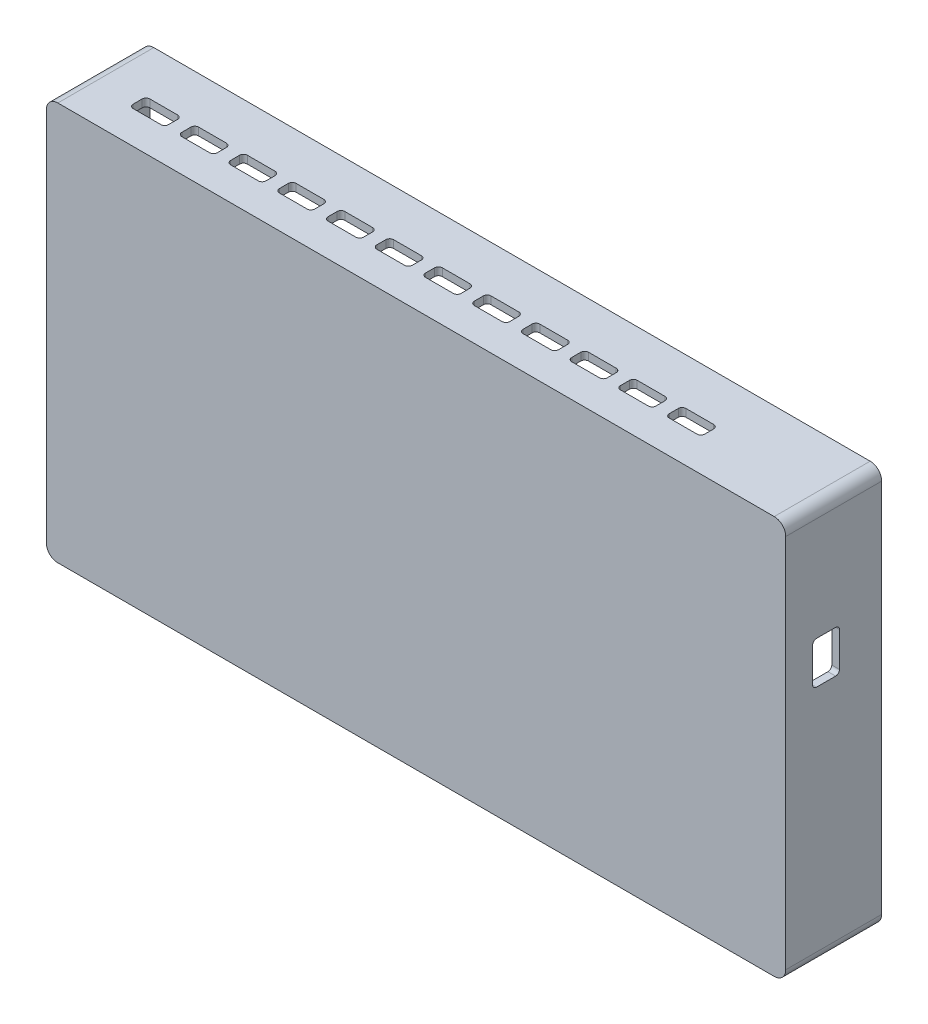
SolidWorks part; units mm, degrees
ref_plane "Front Plane" through (0, 0, 0) normal (0, 0, 1) x (1, 0, 0)
ref_plane "Top Plane" through (0, 0, 0) normal (0, 1, 0) x (1, 0, 0)
ref_plane "Right Plane" through (0, 0, 0) normal (1, 0, 0) x (0, 0, -1)
sketch "Sketch2" plane through (0, 0, 0) normal (0, 0, 1) x (1, 0, 0)
  line L8 (-189.174, -3.5) -> (3.5, -3.5)
  line L9 (3.5, -3.5) -> (3.5, 100.274)
  line L10 (3.5, 100.274) -> (-189.174, 100.274)
  line L11 (-189.174, 100.274) -> (-189.174, -3.5)
  line L12 (-186.174, -3.5) -> (0.5, -3.5)
  line L13 (3.5, -0.5) -> (3.5, 97.274)
  line L14 (0.5, 100.274) -> (-186.174, 100.274)
  line L15 (-189.174, 97.274) -> (-189.174, -0.5)
  arc A0 (-186.174, -3.5) -> (-189.174, -0.5) centre (-186.174, -0.5) cw
  arc A1 (0.5, -3.5) -> (3.5, -0.5) centre (0.5, -0.5) ccw
  arc A2 (3.5, 97.274) -> (0.5, 100.274) centre (0.5, 97.274) ccw
  arc A3 (-186.174, 100.274) -> (-189.174, 97.274) centre (-186.174, 97.274) ccw
  dimension "D2" = 3
  dimension "D1" = 3.5
extrude "Boss-Extrude1" add sketch "Sketch2" along normal blind 2 from offset 5
sketch "Sketch5" plane through (0, 0, 5) normal (0, 0, -1) x (-1, 0, 0)
  circle A0 centre (7.366, 91.059) radius 1.35
  circle A1 centre (7.366, 4.699) radius 1.35
  circle A2 centre (104.648, 42.799) radius 1.35
  circle A3 centre (179.578, 75.565) radius 1.35
  circle A4 centre (179.324, 5.207) radius 1.35
sketch "Sketch11" plane through (0, 0, 5) normal (0, 0, -1) x (-1, 0, 0)
  circle A0 centre (7.366, 91.059) radius 3
  circle A1 centre (7.366, 4.699) radius 3
  circle A2 centre (104.648, 42.799) radius 3
  circle A3 centre (179.324, 5.207) radius 3
  circle A4 centre (179.578, 75.565) radius 3
  dimension "D1" = 6
extrude "Boss-Extrude2" add sketch "Sketch11" along normal blind 3.5
sketch "Sketch12" plane through (0, 0, 1.5) normal (0, 0, -1) x (-1, 0, 0)
  circle A0 centre (7.366, 91.059) radius 1.05
  circle A1 centre (7.366, 4.699) radius 1.05
  circle A3 centre (179.578, 75.565) radius 1.05
  circle A4 centre (179.324, 5.207) radius 1.05
  dimension "D1" = 2.1
extrude "Boss-Extrude3" add sketch "Sketch12" along normal blind 1.5 draft 10
fillet "Fillet2" radius 2 5 edges at (-182.324, 5.207, 5) (-10.366, 4.699, 5) (-107.648, 42.799, 5) (-182.578, 75.565, 5) (-10.366, 91.059, 5)
sketch "Sketch13" plane through (0, 0, 1.5) normal (0, 0, -1) x (-1, 0, 0)
  circle A0 centre (104.648, 42.799) radius 1.6
  dimension "D1" = 3.2
extrude "Cut-Extrude1" cut sketch "Sketch13" against normal blind 3
sketch "Sketch15" plane through (0, 0, 5) normal (0, 0, -1) x (-1, 0, 0)
  line L1 (187.174, -0.5) -> (187.174, 97.274)
  line L2 (186.174, 98.274) -> (-0.5, 98.274)
  line L3 (-1.5, 97.274) -> (-1.5, -0.5)
  line L4 (-0.5, -1.5) -> (186.174, -1.5)
  line L5 (189.174, -0.5) -> (189.174, 97.274)
  line L6 (186.174, 100.274) -> (-0.5, 100.274)
  line L7 (-3.5, 97.274) -> (-3.5, -0.5)
  line L8 (-0.5, -3.5) -> (186.174, -3.5)
  line L9 (189.174, -0.5) -> (189.174, 97.274)
  line L10 (186.174, 100.274) -> (-0.5, 100.274)
  line L11 (-3.5, 97.274) -> (-3.5, -0.5)
  line L12 (-0.5, -3.5) -> (186.174, -3.5)
  arc A0 (187.174, 97.274) -> (186.174, 98.274) centre (186.174, 97.274) ccw
  arc A1 (-0.5, 98.274) -> (-1.5, 97.274) centre (-0.5, 97.274) ccw
  arc A2 (-1.5, -0.5) -> (-0.5, -1.5) centre (-0.5, -0.5) ccw
  arc A3 (186.174, -1.5) -> (187.174, -0.5) centre (186.174, -0.5) ccw
  arc A4 (186.174, -3.5) -> (189.174, -0.5) centre (186.174, -0.5) ccw
  arc A5 (189.174, 97.274) -> (186.174, 100.274) centre (186.174, 97.274) ccw
  arc A6 (-0.5, 100.274) -> (-3.5, 97.274) centre (-0.5, 97.274) ccw
  arc A7 (-3.5, -0.5) -> (-0.5, -3.5) centre (-0.5, -0.5) ccw
  arc A8 (186.174, -3.5) -> (189.174, -0.5) centre (186.174, -0.5) ccw
  arc A9 (189.174, 97.274) -> (186.174, 100.274) centre (186.174, 97.274) ccw
  arc A10 (-0.5, 100.274) -> (-3.5, 97.274) centre (-0.5, 97.274) ccw
  arc A11 (-3.5, -0.5) -> (-0.5, -3.5) centre (-0.5, -0.5) ccw
  dimension "D1" = 0
  dimension "D2" = 2
extrude "Boss-Extrude4" add sketch "Sketch15" along normal blind 23
fillet "Fillet3" radius 1 8 edges at (1.2071, 97.9811, 5) (-92.837, 98.274, 5) (-186.8811, 97.9811, 5) (-187.174, 48.387, 5) (-186.8811, -1.2071, 5) (-92.837, -1.5, 5) (1.2071, -1.2071, 5) (1.5, 48.387, 5)
sketch "Sketch16" plane through (0, 100.274, 0) normal (0, 1, 0) x (1, 0, 0)
  line L5 (-186.174, 18) -> (0.5, 18) construction
  line L8 (-35.3951, 1.5461) -> (-28.1663, 1.5461)
  line L11 (-36.3951, 2.5461) -> (-36.3951, 4.8992)
  line L14 (-35.3951, 5.8992) -> (-28.1663, 5.8992)
  line L17 (-27.1663, 2.5461) -> (-27.1663, 4.8992)
  line L20 (0.5, -7) -> (0.5, 18) construction
  arc A22 (-35.3951, 1.5461) -> (-36.3951, 2.5461) centre (-35.3951, 2.5461) cw
  arc A23 (-28.1663, 1.5461) -> (-27.1663, 2.5461) centre (-28.1663, 2.5461) ccw
  arc A24 (-28.1663, 5.8992) -> (-27.1663, 4.8992) centre (-28.1663, 4.8992) cw
  arc A25 (-36.3951, 4.8992) -> (-35.3951, 5.8992) centre (-35.3951, 4.8992) cw
  point P0 (-36.3951, 3.7226)
  point P1 (-27.1663, 3.7226)
  point P3 (-31.7807, 5.8992)
  point P6 (-30.8579, 18)
  dimension "D2" = 12.1008
  dimension "D1" = 9.2288
  dimension "D3" = 27.6663
extrude "Cut-Extrude2" cut sketch "Sketch16" against normal blind 2
pattern_linear "LPattern1" count 12 spacing 12.7 along (-1, 0, 0) of "Cut-Extrude2"
sketch "Sketch17" plane through (3.5, 0, 0) normal (1, 0, 0) x (0, 0, -1)
  line L0 (-7, 97.274) -> (18, 97.274) construction
  line L1 (0, 59.274) -> (7, 59.274)
  line L2 (0, 59.274) -> (0, 70.274)
  line L3 (0, 70.274) -> (7, 70.274)
  line L4 (7, 59.274) -> (7, 70.274)
  line L5 (-7, -0.5) -> (-7, 97.274) construction
  dimension "D1" = 27
  dimension "D2" = 7
  dimension "D3" = 11
  dimension "D4" = 7
extrude "Cut-Extrude3" cut sketch "Sketch17" against normal blind 2
fillet "Fillet4" radius 1 4 edges at (2.5, 70.274, 0) (2.5, 70.274, -7) (2.5, 59.274, -7) (2.5, 59.274, 0)
